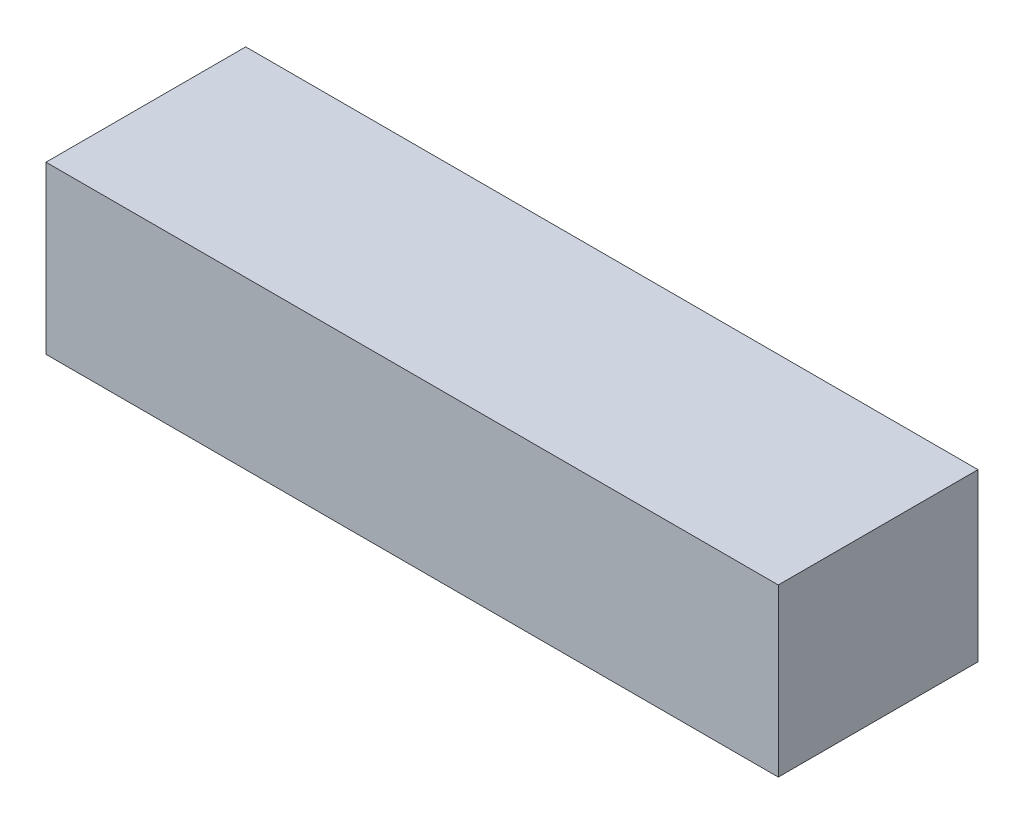
SolidWorks part; units mm, degrees
material "Plain Carbon Steel"
ref_plane "Front Plane" through (0, 0, 0) normal (0, 0, 1) x (1, 0, 0)
ref_plane "Top Plane" through (0, 0, 0) normal (0, 1, 0) x (1, 0, 0)
ref_plane "Right Plane" through (0, 0, 0) normal (1, 0, 0) x (0, 0, -1)
sketch "Sketch1" plane through (0, 0, 0) normal (0, 1, 0) x (1, 0, 0)
  line L1 (-147.2782, 92.1951) -> (72.7218, 92.1951)
  line L2 (-147.2782, 92.1951) -> (-147.2782, 32.1951)
  line L3 (-147.2782, 32.1951) -> (72.7218, 32.1951)
  line L4 (72.7218, 92.1951) -> (72.7218, 32.1951)
  dimension "D1" = 60
  dimension "D2" = 220
extrude "Boss-Extrude1" add sketch "Sketch1" along normal blind 50
